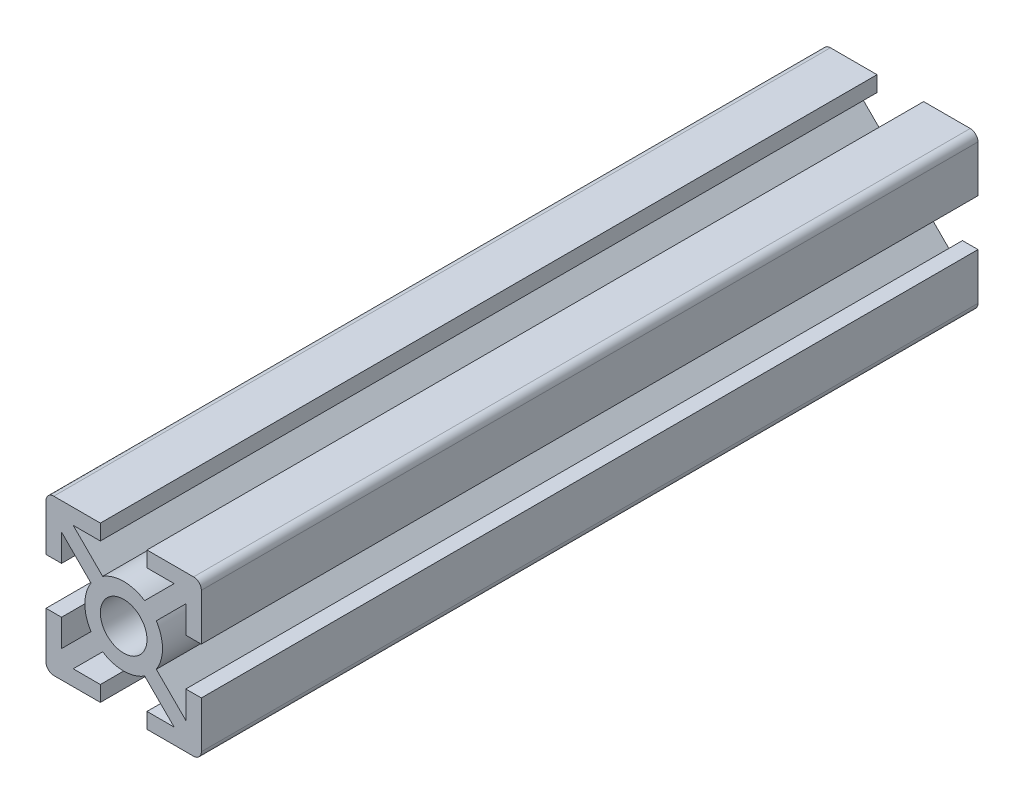
SolidWorks part; units mm, degrees
ref_plane "Alzado" through (0, 0, 0) normal (0, 0, 1) x (1, 0, 0)
ref_plane "Planta" through (0, 0, 0) normal (0, 1, 0) x (1, 0, 0)
ref_plane "Vista lateral" through (0, 0, 0) normal (1, 0, 0) x (0, 0, -1)
sketch "Croquis2" plane through (0, 0, 0) normal (0, 0, 1) x (1, 0, 0)
  line L0 (10, 10) -> (-10, -10) construction
  line L1 (-10, 10) -> (-3, 10)
  line L2 (-10, 10) -> (-10, 3)
  line L3 (-10, -10) -> (-3, -10)
  line L4 (10, 10) -> (10, 3)
  line L5 (6.5, 8) -> (2.7051, 4.2051)
  line L6 (-6.5, 8) -> (-3, 8)
  line L7 (-8, 6.5) -> (-8, 3)
  line L8 (-6.5, -8) -> (-3, -8)
  line L9 (8, 6.5) -> (8, 3)
  line L10 (-6.5, -8) -> (-2.7051, -4.2051)
  line L11 (-8, 6.5) -> (-4.2051, 2.7051)
  line L12 (-6.5, 8) -> (-2.7051, 4.2051)
  line L13 (-3, 10) -> (-3, 8)
  line L14 (3, 10) -> (3, 8)
  line L15 (10, 3) -> (8, 3)
  line L16 (10, -3) -> (8, -3)
  line L17 (3, -8) -> (3, -10)
  line L18 (-3, -8) -> (-3, -10)
  line L19 (-8, -3) -> (-10, -3)
  line L20 (-8, 3) -> (-10, 3)
  line L21 (-10, -3) -> (-10, -10)
  line L22 (-8, -3) -> (-8, -6.5)
  line L23 (3, -8) -> (6.5, -8)
  line L24 (3, -10) -> (10, -10)
  line L25 (10, -3) -> (10, -10)
  line L26 (8, -3) -> (8, -6.5)
  line L27 (4.2051, 2.7051) -> (8, 6.5)
  line L28 (-4.2051, -2.7051) -> (-8, -6.5)
  line L29 (3, 8) -> (6.5, 8)
  line L30 (2.7051, -4.2051) -> (6.5, -8)
  line L31 (3, 10) -> (10, 10)
  line L32 (4.2051, -2.7051) -> (8, -6.5)
  arc A0 (-2.7051, -4.2051) -> (2.7051, -4.2051) centre (0, 0) ccw
  circle A1 centre (0, 0) radius 3
  arc A2 (-4.2051, 2.7051) -> (-4.2051, -2.7051) centre (0, 0) ccw
  arc A3 (2.7051, 4.2051) -> (-2.7051, 4.2051) centre (0, 0) ccw
  arc A4 (4.2051, -2.7051) -> (4.2051, 2.7051) centre (0, 0) ccw
  dimension "D8" = 2.1213
  dimension "D2" = 20
  dimension "D5" = 2
  dimension "D15" = 10
  dimension "D9" = 6
  dimension "D1" = 20
  dimension "D3" = 2
  dimension "D4" = 2
  dimension "D6" = 2
  dimension "D7" = 2.1213
  dimension "D10" = 2.1213
  dimension "D11" = 2.1213
  dimension "D17" = 7
  dimension "D18" = 7
  dimension "D19" = 7
  dimension "D20" = 7
  dimension "D21" = 7
  dimension "D22" = 7
  dimension "D23" = 7
  dimension "D24" = 7
extrude "Saliente-Extruir2" add sketch "Croquis2" along normal blind 100
fillet "Redondeo2" radius 1 4 edges at (-10, -10, 50) (10, -10, 50) (10, 10, 50) (-10, 10, 50)
